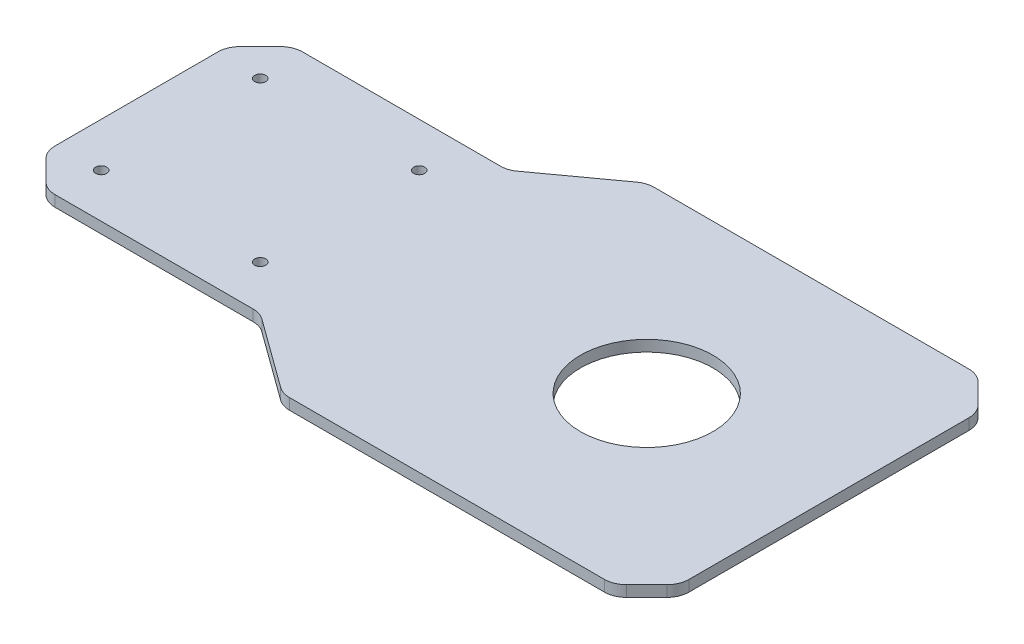
SolidWorks part; units mm, degrees
material "Alumina"
ref_plane "Front Plane" through (0, 0, 0) normal (0, 0, 1) x (1, 0, 0)
ref_plane "Top Plane" through (0, 0, 0) normal (0, 1, 0) x (1, 0, 0)
ref_plane "Right Plane" through (0, 0, 0) normal (1, 0, 0) x (0, 0, -1)
sketch "Sketch2" plane through (0, 0, 0) normal (0, 1, 0) x (1, 0, 0)
  line L0 (56, 56) -> (92.5, 82.5)
  line L1 (-56, 56) -> (56, 56)
  line L2 (-56, 56) -> (-56, -56)
  line L3 (-56, -56) -> (56, -56)
  line L4 (56, 56) -> (56, -56) construction
  line L5 (-56, 56) -> (56, -56) construction
  line L6 (-56, -56) -> (56, 56) construction
  line L7 (92.5, 82.5) -> (257.5, 82.5)
  line L8 (92.5, 82.5) -> (92.5, -82.5) construction
  line L9 (92.5, -82.5) -> (257.5, -82.5)
  line L10 (257.5, 82.5) -> (257.5, -82.5)
  line L11 (92.5, 82.5) -> (257.5, -82.5) construction
  line L12 (92.5, -82.5) -> (257.5, 82.5) construction
  line L13 (56, -56) -> (92.5, -82.5)
  point P0 (0, 0)
  point P1 (175, 0)
  point P3 (175, 0)
  point P5 (0, 0)
  dimension "D1" = 175
  dimension "D2" = 112
  dimension "D3" = 165
extrude "Boss-Extrude1" add sketch "Sketch2" along normal blind 5
chamfer "Chamfer1" distance 15 angle 45 4 edges at (-56, 2.5, -56) (-56, 2.5, 56) (257.5, 2.5, -82.5) (257.5, 2.5, 82.5)
fillet "Fillet1" radius 10 12 edges at (56, 2.5, 56) (56, 2.5, -56) (92.5, 2.5, -82.5) (92.5, 2.5, 82.5) (-56, 2.5, 41) (-41, 2.5, 56) (-56, 2.5, -41) (-41, 2.5, -56) (242.5, 2.5, -82.5) (257.5, 2.5, -67.5) (257.5, 2.5, 67.5) (242.5, 2.5, 82.5)
sketch "Sketch3" plane through (0, 5, 0) normal (0, 1, 0) x (1, 0, 0)
  circle A0 centre (36, 36) radius 2.5
  circle A1 centre (-36, 36) radius 2.5
  circle A2 centre (-36, -36) radius 2.5
  circle A3 centre (36, -36) radius 2.5
  circle A4 centre (175, 0) radius 30
  point P3 (0, 0)
  dimension "D1" = 5
  dimension "D8" = 60
  dimension "D2" = 36
  dimension "D3" = 36
  dimension "D6" = 72
  dimension "D7" = 72
  dimension "D9" = 175
  dimension "D4" = 2
  dimension "D5" = 2
extrude "Cut-Extrude1" cut sketch "Sketch3" against normal through all
equation "\"Drive Pulley Diameter\"= 50mm"
equation "\"Transfer Pulley Diameter\"= 100mm"
equation "\"Belt Distance\"= 175mm"
equation "\"Extra Spacing\"= 15mm"
equation "\"Drive Pulley Radius\"= \"Drive Pulley Diameter\" / 2"
equation "\"Transfer Pulley Radius\"= \"Transfer Pulley Diameter\" / 2"
equation "\"Base Thickness\"= 5mm"
equation "\"Stepper Mount Width\"= 97mm"
equation "\"D2@Sketch2\"=\"Stepper Mount Width\"+\"Extra Spacing\""
equation "\"Elevator Diameter\"= 150mm"
equation "\"D3@Sketch2\"=\"Elevator Diameter\"+\"Extra Spacing\""
equation "\"Motor Mount Screw Diameter\"= 5mm"
equation "\"D1@Sketch3\"=\"Motor Mount Screw Diameter\""
equation "\"Motor Mount Screw X-Dist\"= 72 / 2mm"
equation "\"Motor Mount Screw Y-Dist\"= 72 / 2mm"
equation "\"D2@Sketch3\"=\"Motor Mount Screw Y-Dist\""
equation "\"D6@Sketch3\"=\"Motor Mount Screw X-Dist\"*2"
equation "\"D7@Sketch3\"=\"Motor Mount Screw Y-Dist\"*2"
equation "\"Bearing Diameter\"= 60mm"
equation "\"D9@Sketch3\"=\"Belt Distance\""
equation "\"D8@Sketch3\"=\"Bearing Diameter\""
